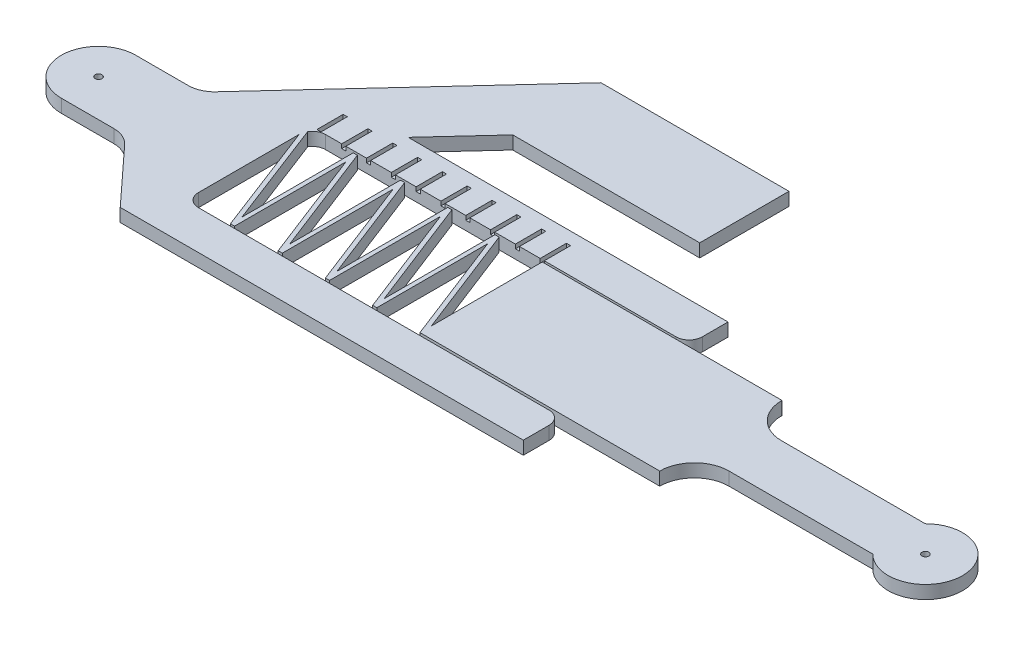
SolidWorks part; units mm, degrees
ref_plane "Front Plane" through (0, 0, 0) normal (0, 0, 1) x (1, 0, 0)
ref_plane "Top Plane" through (0, 0, 0) normal (0, 1, 0) x (1, 0, 0)
ref_plane "Right Plane" through (0, 0, 0) normal (1, 0, 0) x (0, 0, -1)
sketch "Hole-to-Hole Full Length" plane through (0, 0, 0) normal (0, 1, 0) x (1, 0, 0)
  line L0 (0, 0) -> (-200.0001, 0) construction
  dimension "D1" = 200.0001
sketch "Hole-to-Hole Min Length" plane through (0, 0, 0) normal (0, 1, 0) x (1, 0, 0)
  line L0 (0, 0) -> (-143, 0) construction
  line L1 (0, 0) -> (-200.0001, 0) construction
  point P5 (0, 0)
  dimension "D1" = 143
sketch "Sketch3" plane through (0, 0, 0) normal (0, 1, 0) x (1, 0, 0)
  line L0 (-170.0001, -24.75) -> (-170.0001, 24.75) construction
  line L1 (-200.0001, 9) -> (-187.3001, 9)
  line L2 (-182.6309, 11.0464) -> (-170.0001, 24.75)
  line L3 (0, -6.35) -> (0, 6.35)
  line L4 (0, 6.35) -> (-41.1481, 6.35)
  line L7 (-143, 0) -> (-221.4388, 0) construction
  line L8 (-200.0001, -9) -> (-187.3001, -9)
  line L9 (-182.6309, -11.0464) -> (-170.0001, -24.75)
  line L10 (-170.0001, 24.75) -> (-72.5001, 24.75)
  line L11 (-72.5001, 24.75) -> (-72.5001, 18.525)
  line L12 (-75.6751, 15.35) -> (-160.4751, 15.35)
  line L13 (-163.6501, 12.175) -> (-163.6501, -12.175)
  line L14 (-72.5001, -24.75) -> (-72.5001, -18.525)
  line L15 (-170.0001, -24.75) -> (-72.5001, -24.75)
  line L16 (-75.6751, -15.35) -> (-160.4751, -15.35)
  line L17 (-163.6501, 12.175) -> (-153.2501, -14.85)
  line L18 (-153.2501, -14.85) -> (-152.2501, -14.85)
  line L19 (-152.2501, -14.85) -> (-152.2501, 14.85)
  line L20 (-152.2501, 14.85) -> (-153.2501, 14.85)
  line L21 (-153.2501, 14.85) -> (-153.2501, -12.0657)
  line L22 (-153.2501, -12.0657) -> (-155.8607, -5.2818)
  line L23 (-155.8607, -5.2818) -> (-163.2035, 13.7988)
  line L24 (-152.2501, 14.85) -> (-141.8201, -11.9727)
  line L25 (-141.8201, -11.9727) -> (-141.8201, 14.85)
  line L26 (-141.8201, 14.85) -> (-140.8201, 14.85)
  line L27 (-140.8201, 14.85) -> (-140.8201, -14.732)
  line L28 (-140.8201, -14.732) -> (-141.8201, -14.732)
  line L29 (-141.8201, -14.732) -> (-152.2501, 12.0907)
  line L30 (-140.8201, 14.85) -> (-130.3901, -11.9727)
  line L31 (-130.3901, -14.732) -> (-140.8201, 12.0907)
  line L32 (-129.3901, -14.732) -> (-130.3901, -14.732)
  line L33 (-129.3901, 14.85) -> (-129.3901, -14.732)
  line L34 (-130.3901, -11.9727) -> (-130.3901, 14.85)
  line L35 (-130.3901, 14.85) -> (-129.3901, 14.85)
  line L36 (-129.3901, 14.85) -> (-118.9601, -11.9727)
  line L37 (-118.9601, -14.732) -> (-129.3901, 12.0907)
  line L38 (-117.9601, -14.732) -> (-118.9601, -14.732)
  line L39 (-117.9601, 14.85) -> (-117.9601, -14.732)
  line L40 (-118.9601, -11.9727) -> (-118.9601, 14.85)
  line L41 (-118.9601, 14.85) -> (-117.9601, 14.85)
  line L42 (-117.9601, 14.85) -> (-107.5301, -11.9727)
  line L43 (-107.5301, -14.732) -> (-117.9601, 12.0907)
  line L44 (-106.5301, -14.732) -> (-107.5301, -14.732)
  line L45 (-106.5301, 14.85) -> (-49.5301, 14.85)
  line L46 (-107.5301, -11.9727) -> (-107.5301, 14.85)
  line L47 (-107.5301, 14.85) -> (-106.5301, 14.85)
  line L48 (-18.4597, 2.9526) -> (0.5643, 9.8767) construction
  line L49 (-106.5301, -14.732) -> (-49.5301, -14.732)
  line L50 (-49.5301, 14.85) -> (-49.5301, 14.732)
  line L51 (-170.0001, 24.75) -> (-137.9706, 59.5)
  line L52 (-137.9706, 59.5) -> (-92.5001, 59.5)
  line L53 (0, -6.35) -> (-41.1481, -6.35)
  line L54 (-106.5301, 14.85) -> (-106.5301, -14.732) [skipped]
  line L55 (-92.5001, 59.5) -> (-92.5001, 37.91)
  line L56 (-92.5001, 37.91) -> (-137.7199, 37.91)
  line L57 (-137.7199, 37.91) -> (-149.8497, 24.75)
  circle A0 centre (-200.0001, 0) radius 9
  arc A1 (-182.6309, 11.0464) -> (-187.3001, 9) centre (-187.3001, 15.35) cw
  arc A2 (-182.6309, -11.0464) -> (-187.3001, -9) centre (-187.3001, -15.35) ccw
  arc A3 (-72.5001, 18.525) -> (-75.6751, 15.35) centre (-75.6751, 18.525) cw
  arc A4 (-160.4751, 15.35) -> (-163.6501, 12.175) centre (-160.4751, 12.175) ccw
  arc A5 (-72.5001, -18.525) -> (-75.6751, -15.35) centre (-75.6751, -18.525) ccw
  arc A6 (-160.4751, -15.35) -> (-163.6501, -12.175) centre (-160.4751, -12.175) cw
  arc A7 (-41.1481, 6.35) -> (-49.5301, 14.732) centre (-41.1481, 14.732) cw
  arc A8 (-41.1481, -6.35) -> (-49.5301, -14.732) centre (-41.1481, -14.732) ccw
  circle A9 centre (0, 0) radius 9
  circle A10 centre (0, 0) radius 0.8255
  circle A11 centre (-200.0001, 0) radius 0.8255
  spline S0 degree 3 poles (-3.3582, 8.35) (-3.9399, 8.1992) (-4.649, 8.0154) (-8.0352, 6.7059) (-10.6038, 6.5099) (-12.7, 6.35) knots 0 0 0 0 0.456205 0.556205 1 1 1 1
  spline S1 degree 3 poles (-3.3582, -8.35) (-3.9399, -8.1992) (-4.649, -8.0154) (-8.0352, -6.7059) (-10.6038, -6.5099) (-12.7, -6.35) knots 0 0 0 0 0.456205 0.556205 1 1 1 1
  point P2 (-170.0001, 0)
  point P7 (0, 0)
  point P35 (-163.6501, 0)
  point P57 (0, 0)
  point P89 (-6.3779, 6.35)
  dimension "D4" = 18
  dimension "D5" = 6.35
  dimension "D9" = 3.175
  dimension "D10" = 3.175
  dimension "D23" = 20
  dimension "D24" = 10.7177
  dimension "D26" = 1.651
  dimension "D3" = 8.382
  dimension "D1" = 49.5
  dimension "D2" = 30
  dimension "D6" = 12.7
  dimension "D7" = 1
  dimension "D8" = 6.35
  dimension "D11" = 1
  dimension "D12" = 0.5
  dimension "D13" = 0.5
  dimension "D14" = 11.4
  dimension "D15" = 107.5
  dimension "D16" = 2
  dimension "D17" = 1
  dimension "D18" = 11.43
  dimension "D19" = 1
  dimension "D21" = 127.5
  dimension "D22" = 12.7
  dimension "D25" = 1
  dimension "D27" = 57
  dimension "D28" = 6.35
  dimension "D29" = 59.5
  dimension "D30" = 21.59
  dimension "D31" = 14.8167
  dimension "D20" = 4
extrude "Boss-Extrude1" add sketch "Sketch3" along normal blind 3.175 contours L57 L56 L55 L52 L51 L10 | L16 A6 L13 A4 L12 A3 L11 L10 L2 A1 L1 A0 L8 A2 L9 L15 L14 A5 | A0 A11 | A10 L3 L53 A9 L4 | A10 L3 L4 A9 L53 | A9 L4 A7 L50 L45 L47 L46 L42 L39 L43 L44 L49 A8 L53 | L23 A4 L17 L18 L19 L20 L21 L22 | L29 L28 L27 L26 L25 L24 L19 | L35 L34 L30 L27 L31 L32 L33 | L41 L40 L36 L33 L37 L38 L39
sketch "Sketch4" plane through (0, 3.175, 0) normal (0, 1, 0) x (1, 0, 0)
  line L0 (-107.5301, 15.35) -> (-107.5301, 21.7)
  line L1 (-107.5301, 21.7) -> (-108.5301, 21.7)
  line L2 (-108.5301, 21.7) -> (-108.5301, 15.35)
  line L3 (-108.5301, 15.35) -> (-107.5301, 15.35)
  line L4 (-107.5301, -11.9727) -> (-107.5301, 14.85) construction
  line L5 (-75.6751, 15.35) -> (-160.4751, 15.35) construction
  line L6 (-113.5301, 21.7) -> (-114.5301, 21.7)
  line L7 (-113.5301, 15.35) -> (-113.5301, 21.7)
  line L8 (-114.5301, 15.35) -> (-113.5301, 15.35)
  line L9 (-114.5301, 21.7) -> (-114.5301, 15.35)
  line L10 (-119.5301, 21.7) -> (-120.5301, 21.7)
  line L11 (-119.5301, 15.35) -> (-119.5301, 21.7)
  line L12 (-120.5301, 15.35) -> (-119.5301, 15.35)
  line L13 (-120.5301, 21.7) -> (-120.5301, 15.35)
  line L14 (-125.5301, 21.7) -> (-126.5301, 21.7)
  line L15 (-125.5301, 15.35) -> (-125.5301, 21.7)
  line L16 (-126.5301, 15.35) -> (-125.5301, 15.35)
  line L17 (-126.5301, 21.7) -> (-126.5301, 15.35)
  line L18 (-131.5301, 21.7) -> (-132.5301, 21.7)
  line L19 (-131.5301, 15.35) -> (-131.5301, 21.7)
  line L20 (-132.5301, 15.35) -> (-131.5301, 15.35)
  line L21 (-132.5301, 21.7) -> (-132.5301, 15.35)
  line L22 (-137.5301, 21.7) -> (-138.5301, 21.7)
  line L23 (-137.5301, 15.35) -> (-137.5301, 21.7)
  line L24 (-138.5301, 15.35) -> (-137.5301, 15.35)
  line L25 (-138.5301, 21.7) -> (-138.5301, 15.35)
  line L26 (-143.5301, 21.7) -> (-144.5301, 21.7)
  line L27 (-143.5301, 15.35) -> (-143.5301, 21.7)
  line L28 (-144.5301, 15.35) -> (-143.5301, 15.35)
  line L29 (-144.5301, 21.7) -> (-144.5301, 15.35)
  line L30 (-149.5301, 21.7) -> (-150.5301, 21.7)
  line L31 (-149.5301, 15.35) -> (-149.5301, 21.7)
  line L32 (-150.5301, 15.35) -> (-149.5301, 15.35)
  line L33 (-150.5301, 21.7) -> (-150.5301, 15.35)
  line L34 (-155.5301, 21.7) -> (-156.5301, 21.7)
  line L35 (-155.5301, 15.35) -> (-155.5301, 21.7)
  line L36 (-156.5301, 15.35) -> (-155.5301, 15.35)
  line L37 (-156.5301, 21.7) -> (-156.5301, 15.35)
  line L38 (-161.5301, 21.7) -> (-162.5301, 21.7)
  line L39 (-161.5301, 15.35) -> (-161.5301, 21.7)
  line L40 (-162.5301, 15.35) -> (-161.5301, 15.35)
  line L41 (-162.5301, 21.7) -> (-162.5301, 15.35)
  dimension "D1" = 1
  dimension "D2" = 0
  dimension "D3" = 6.35
  dimension "D4" = 10
  dimension "D5" = 5
extrude "Cut-Extrude1" cut sketch "Sketch4" against normal blind 1
